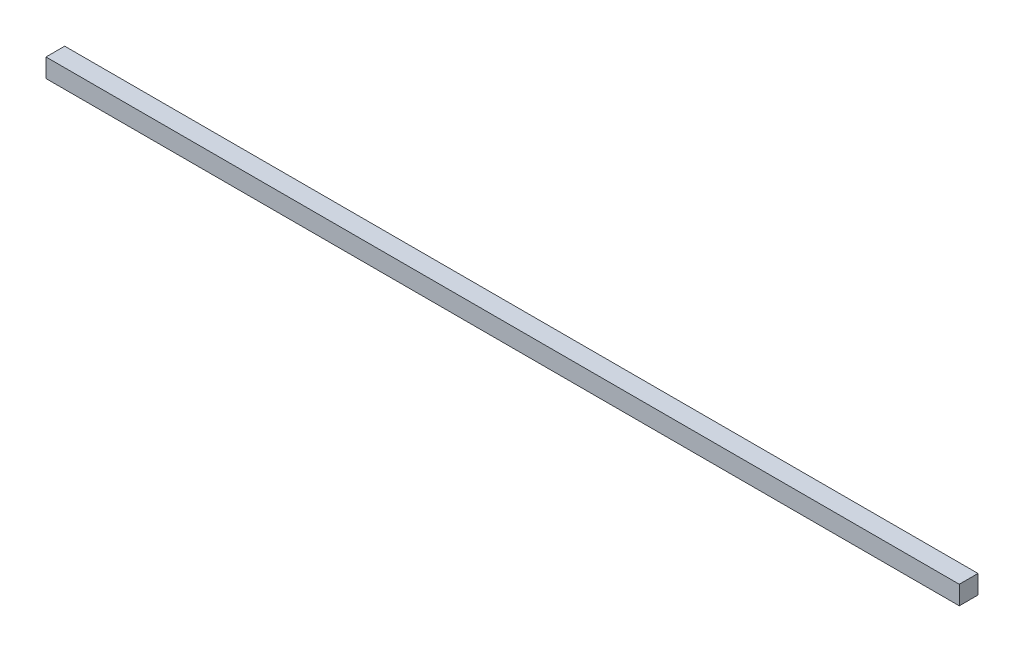
SolidWorks part; units mm, degrees
material "Бальса"
ref_plane "Спереди" through (0, 0, 0) normal (0, 0, 1) x (1, 0, 0)
ref_plane "Сверху" through (0, 0, 0) normal (0, 1, 0) x (1, 0, 0)
ref_plane "Справа" through (0, 0, 0) normal (1, 0, 0) x (0, 0, -1)
sketch "Эскиз1" plane through (0, 0, 0) normal (0, 0, 1) x (1, 0, 0)
  line L1 (0, 0) -> (2440, 0)
  line L2 (0, 0) -> (0, 50)
  line L3 (0, 50) -> (2440, 50)
  line L4 (2440, 0) -> (2440, 50)
  line L5 (2440, -800) -> (2440, 100) construction
  dimension "D1" = 50
extrude "Бобышка-Вытянуть1" add sketch "Эскиз1" along normal blind 50
equation "\"D1@Бобышка-Вытянуть1\"=\"D1@Эскиз1\""
